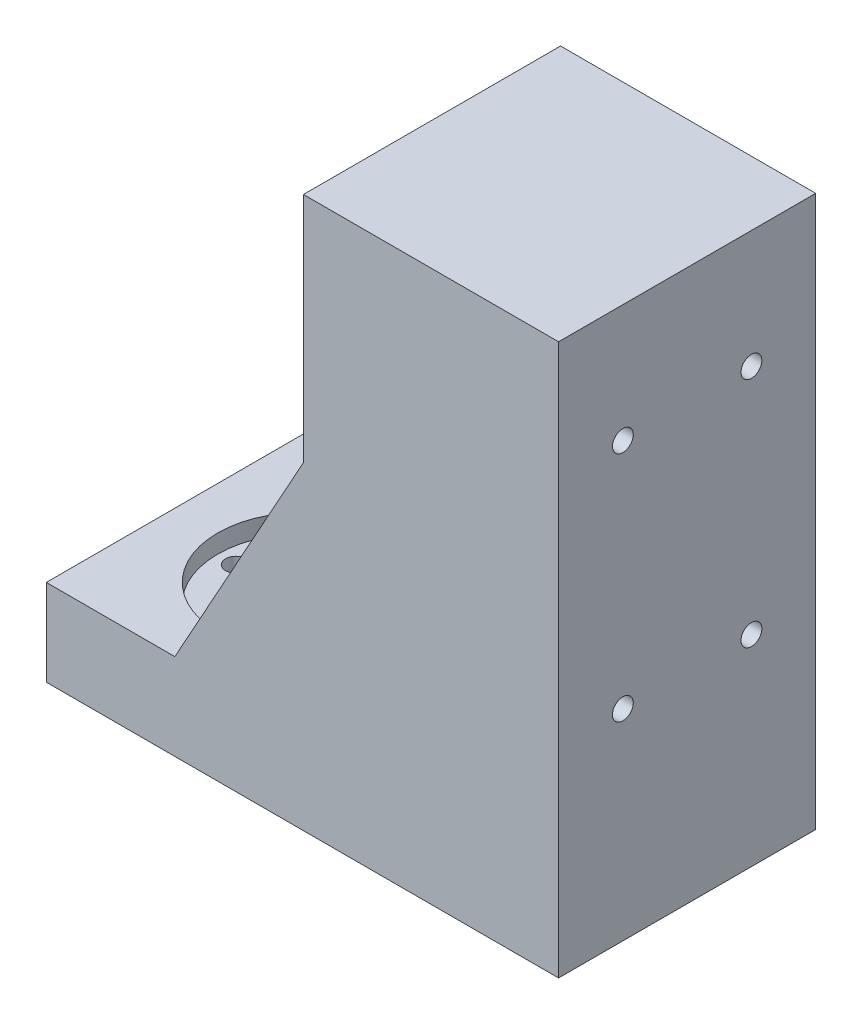
SolidWorks part; units mm, degrees
ref_plane "Front Plane" through (0, 0, 0) normal (0, 0, 1) x (1, 0, 0)
ref_plane "Top Plane" through (0, 0, 0) normal (0, 1, 0) x (1, 0, 0)
ref_plane "Right Plane" through (0, 0, 0) normal (1, 0, 0) x (0, 0, -1)
sketch "Sketch1" plane through (0, 0, 0) normal (0, 0, 1) x (1, 0, 0)
  line L0 (0, 0) -> (42, 0)
  line L1 (0, 0) -> (0, -14.1208)
  line L2 (0, -14.1208) -> (42, -14.1208)
  line L3 (42, -14.1208) -> (83.679, -14.1208)
  line L4 (83.679, -14.1208) -> (83.679, 75.8792)
  line L5 (83.679, 75.8792) -> (42, 75.8792)
  line L6 (42, 75.8792) -> (42, 0)
  dimension "D1" = 42
  dimension "D2" = 14.1208
  dimension "D3" = 90
  dimension "D4" = 41.679
extrude "Boss-Extrude1" add sketch "Sketch1" along normal blind 42
sketch "Sketch3" plane through (0, 0, 0) normal (0, 1, 0) x (1, 0, 0)
  line L0 (21, 0) -> (21, -42) construction
  line L1 (42, 0) -> (0, 0) construction
  line L2 (42, -42) -> (0, -42) construction
  circle A0 centre (21, -21) radius 3
  dimension "D1" = 6
extrude "Cut-Extrude1" cut sketch "Sketch3" against normal blind 14.1208
sketch "Sketch4" plane through (0, 0, 0) normal (0, 1, 0) x (1, 0, 0)
  circle A0 centre (21, -21) radius 14
  dimension "D1" = 28
extrude "Cut-Extrude3" cut sketch "Sketch4" against normal blind 3
sketch "Sketch5" plane through (0, 0, 0) normal (0, 1, 0) x (1, 0, 0)
  circle A0 centre (21, -21) radius 9
  dimension "D1" = 18
extrude "Cut-Extrude4" cut sketch "Sketch5" against normal blind 5
sketch "Sketch6" plane through (0, -3, 0) normal (0, 1, 0) x (1, 0, 0)
  line L0 (21, 0) -> (21, -42) construction
  line L1 (42, 0) -> (0, 0) construction
  line L2 (42, -42) -> (0, -42) construction
  line L3 (0, -21) -> (42, -21) construction
  line L4 (0, -42) -> (0, 0) construction
  line L5 (42, -42) -> (42, 0) construction
  circle A0 centre (21, -21) radius 11 construction
  circle A1 centre (21, -10) radius 1.7
  circle A2 centre (32, -21) radius 1.7
  circle A3 centre (21, -32) radius 1.7
  circle A4 centre (10, -21) radius 1.7
  dimension "D1" = 22
  dimension "D2" = 3.4
  dimension "D3" = 3.4
  dimension "D4" = 3.4
  dimension "D5" = 3.4
extrude "Cut-Extrude5" cut sketch "Sketch6" against normal blind 11.41
sketch "Sketch7" plane through (42, 0, 0) normal (-1, 0, 0) x (0, 0, 1)
  line L0 (21, 75.8792) -> (21, 37.4292) construction
  line L1 (42, 75.8792) -> (0, 75.8792) construction
  line L2 (21, 37.4292) -> (42, 37.4292) construction
  line L3 (42, 75.8792) -> (42, 0) construction
  line L4 (21, 37.4292) -> (0, 37.4292) construction
  line L5 (0, 75.8792) -> (0, 0) construction
  line L6 (21, 37.4292) -> (21, 0) construction
  line L7 (42, 0) -> (0, 0) construction
  line L8 (10.5, 37.4292) -> (10.5, 0) construction
  line L9 (31.5, 37.4292) -> (31.5, 0) construction
  line L10 (10.5, 37.4292) -> (10.5, 75.8792) construction
  line L11 (31.5, 37.4292) -> (31.5, 75.8792) construction
  circle A0 centre (10.5, 56.6542) radius 1.7
  circle A1 centre (31.5, 56.6542) radius 1.7
  circle A2 centre (10.5, 18.7146) radius 1.7
  circle A3 centre (31.5, 18.7146) radius 1.7
  dimension "D2" = 3.4
  dimension "D3" = 3.4
  dimension "D4" = 3.4
  dimension "D5" = 3.4
  dimension "D1" = 38.45
extrude "Cut-Extrude6" cut sketch "Sketch7" against normal blind 41.679
sketch "Sketch8" plane through (0, 0, 42) normal (0, 0, 1) x (1, 0, 0)
  line L0 (42, 37.9396) -> (21, 0)
  line L1 (42, 75.8792) -> (42, 0) construction
  line L2 (42, 0) -> (0, 0) construction
  line L3 (21, 0) -> (42, 0)
  line L4 (42, 0) -> (42, 37.9396)
extrude "Boss-Extrude2" add sketch "Sketch8" against normal blind 2
sketch "Sketch9" plane through (0, 0, 0) normal (0, 0, -1) x (-1, 0, 0)
  line L0 (-42, 37.9396) -> (-21, 0)
  line L1 (-42, 75.8792) -> (-42, 0) construction
  line L2 (-21, 0) -> (-42, 0)
  line L3 (-21, 0) -> (-42, 0) construction
  line L4 (-42, 0) -> (-42, 37.9396) construction
  line L5 (-42, 0) -> (-42, 37.9396)
extrude "Boss-Extrude3" add sketch "Sketch9" against normal blind 2
equation "\"b\" = 42mm'base of F1"
equation "\"L1\"= 42mm'Length of F1"
equation "\"SF\" = 3'Safety Factor"
equation "\"D\"= 0.3mm'Deflection"
equation "\"P\"= 300'Force in Newtons"
equation "\"SY\"= 30'Yield Strength in MPa"
equation "\"E\"= 1790'Elasticity in MPa"
equation "\"M1\" = 6000'Moment of feature 1 (N*mm)"
equation "\"F1(hs)\"= ( ( 6 * \"M1\" * \"SF\" ) / ( \"b\" * \"SY\" ) ) ^ ( 1 / 2 )'Height Stress for F1"
equation "\"F1(hd)\"= ( ( 6 * \"M1\" * \"L1\" ^ 2 ) / ( \"b\" * \"E\" * \"D\" ) ) ^ ( 1 / 3 )'Height Deflection for F1"
equation "\"L2\"= 90mm'Length of F2"
equation "\"M2\" = 33600'Moment of feature 2 (N*mm)"
equation "\"F2(hs)\"= ( ( 6 * \"M2\" * \"SF\" ) / ( \"b\" * \"SY\" ) ) ^ ( 1 / 2 )'Height Stress for F2"
equation "\"F2(hd)\"= ( ( 6 * \"M2\" * \"L2\" ^ 2 ) / ( \"b\" * \"E\" * \"D\" ) ) ^ ( 1 / 3 )'Height Deflection for F2"
equation "\"D1@Sketch1\"=\"b\""
equation "\"D2@Sketch1\"=\"F1(hd)\""
equation "\"D3@Sketch1\"=\"L2\""
equation "\"D4@Sketch1\"=\"F2(hd)\""
equation "\"D1@Boss-Extrude1\"=\"L1\""
equation "\"D1@Cut-Extrude1\"=\"F1(hd)\""
equation "\"D1@Cut-Extrude6\"=\"F2(hd)\""
